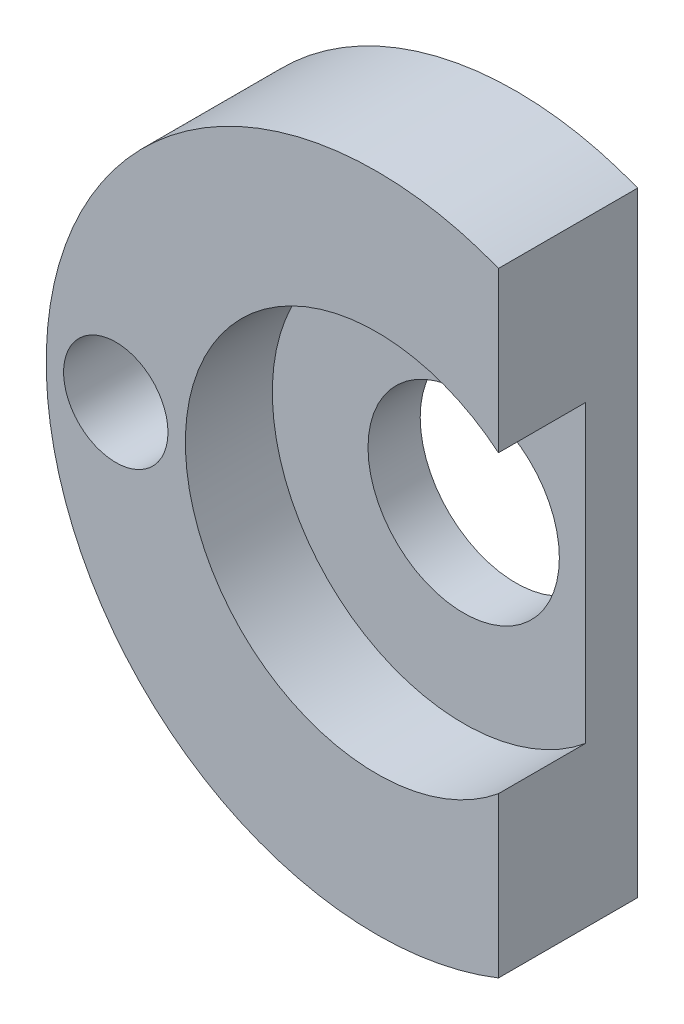
SolidWorks part; units mm, degrees
ref_plane "Plan de face" through (0, 0, 0) normal (0, 0, 1) x (1, 0, 0)
ref_plane "Plan de dessus" through (0, 0, 0) normal (0, 1, 0) x (1, 0, 0)
ref_plane "Plan de droite" through (0, 0, 0) normal (1, 0, 0) x (0, 0, -1)
sketch "Esquisse1" plane through (0, 0, 0) normal (0, 0, 1) x (1, 0, 0)
  circle A0 centre (0, 0) radius 9.5
  circle A1 centre (0, 0) radius 2.75
  circle A2 centre (-7.5, 0) radius 1.5
  point P6 (-7.5, 0)
  dimension "D1" = 19
  dimension "D2" = 5.5
  dimension "D3" = 3
  dimension "D4" = 7.5
extrude "Boss.-Extru.1" add sketch "Esquisse1" along normal blind 4
sketch "Esquisse2" plane through (0, 0, 4) normal (0, 0, 1) x (1, 0, 0)
  line L1 (3.5, 8.8318) -> (9.5, 8.8318)
  line L2 (3.5, 8.8318) -> (3.5, -8.8318)
  line L3 (3.5, -8.8318) -> (9.5, -8.8318)
  line L4 (9.5, 8.8318) -> (9.5, -8.8318)
  circle A0 centre (0, 0) radius 9.5 construction
  point P6 (0, 0)
  dimension "D1" = 6
extrude "Enlèv. mat.-Extru.1" cut sketch "Esquisse2" against normal through all
sketch "Esquisse3" plane through (0, 0, 4) normal (0, 0, 1) x (1, 0, 0)
  circle A0 centre (0, 0) radius 5.5
  point P2 (0, 0)
  dimension "D1" = 11
extrude "Enlèv. mat.-Extru.2" cut sketch "Esquisse3" against normal blind 2.5
